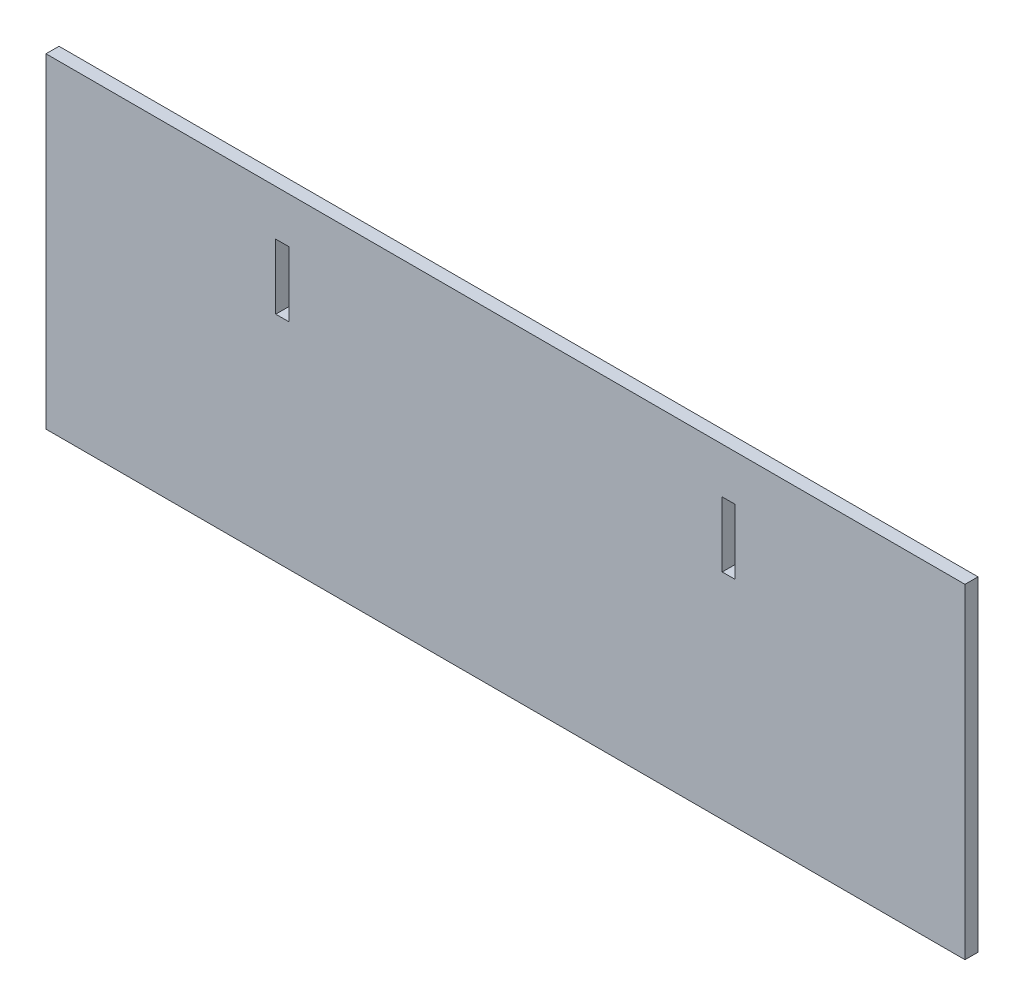
SolidWorks part; units mm, degrees
ref_plane "Front Plane" through (0, 0, 0) normal (0, 0, 1) x (1, 0, 0)
ref_plane "Top Plane" through (0, 0, 0) normal (0, 1, 0) x (1, 0, 0)
ref_plane "Right Plane" through (0, 0, 0) normal (1, 0, 0) x (0, 0, -1)
sketch "Sketch1" plane through (0, 0, 0) normal (0, 0, 1) x (1, 0, 0)
  line L1 (0, 0) -> (212, 0)
  line L2 (0, 0) -> (0, 75)
  line L3 (0, 75) -> (212, 75)
  line L4 (212, 0) -> (212, 75)
  line L5 (53, 64.4722) -> (56, 64.4722)
  line L6 (53, 64.4722) -> (53, 49.4722)
  line L7 (53, 49.4722) -> (56, 49.4722)
  line L8 (56, 64.4722) -> (56, 49.4722)
  line L9 (156, 64.4722) -> (159, 64.4722)
  line L10 (156, 64.4722) -> (156, 49.4722)
  line L11 (156, 49.4722) -> (159, 49.4722)
  line L12 (159, 64.4722) -> (159, 49.4722)
  dimension "D1" = 3
  dimension "D2" = 15
  dimension "D3" = 212
  dimension "D4" = 15
  dimension "D5" = 3
  dimension "D6" = 53
  dimension "D7" = 100
  dimension "D8" = 53
  dimension "D9" = 75
  dimension "D10" = 10.5278
  dimension "D11" = 10.5278
extrude "Boss-Extrude1" add sketch "Sketch1" along normal blind 3
